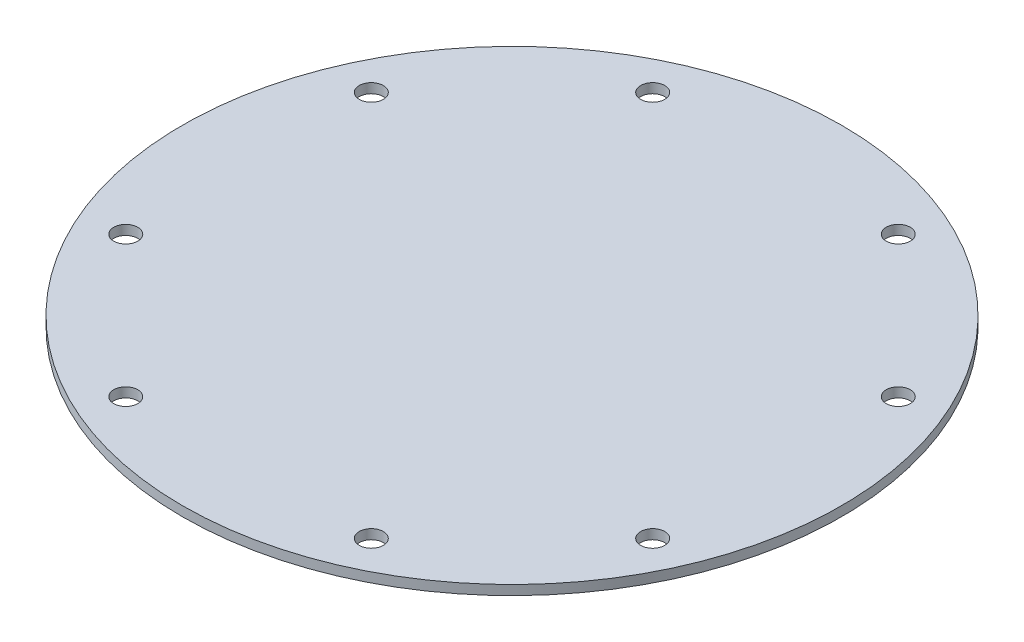
SolidWorks part; units mm, degrees
ref_plane "Front Plane" through (0, 0, 0) normal (0, 0, 1) x (1, 0, 0)
ref_plane "Top Plane" through (0, 0, 0) normal (0, 1, 0) x (1, 0, 0)
ref_plane "Right Plane" through (0, 0, 0) normal (1, 0, 0) x (0, 0, -1)
sketch "Sketch1" plane through (0, 0, 0) normal (0, 1, 0) x (1, 0, 0)
  circle A0 centre (0, 0) radius 86.9315
extrude "Boss-Extrude1" add sketch "Sketch1" along normal blind 2.54
sketch "Sketch3" plane through (0, 2.54, 0) normal (0, 1, 0) x (1, 0, 0)
  line L0 (0, 86.9315) -> (0, -86.9315) construction
  line L1 (86.9315, 0) -> (-86.9315, 0)
  circle A1 centre (-32.385, 69.5007) radius 3.175
  circle A2 centre (32.385, 69.5007) radius 3.175
  circle A3 centre (69.5007, 32.385) radius 3.175
  circle A4 centre (69.5007, -32.385) radius 3.175
  circle A5 centre (32.385, -69.5007) radius 3.175
  circle A6 centre (-32.385, -69.5007) radius 3.175
  circle A7 centre (-69.5007, -32.385) radius 3.175
  circle A8 centre (-69.5007, 32.385) radius 3.175
  circle A9 centre (0, 0) radius 86.9315 construction
  point P15 (0, 0)
extrude "Cut-Extrude1" cut sketch "Sketch3" against normal blind 203.2 contours A5 | A4 | A3 | A2 | A1 | A8 | A7 | A6
